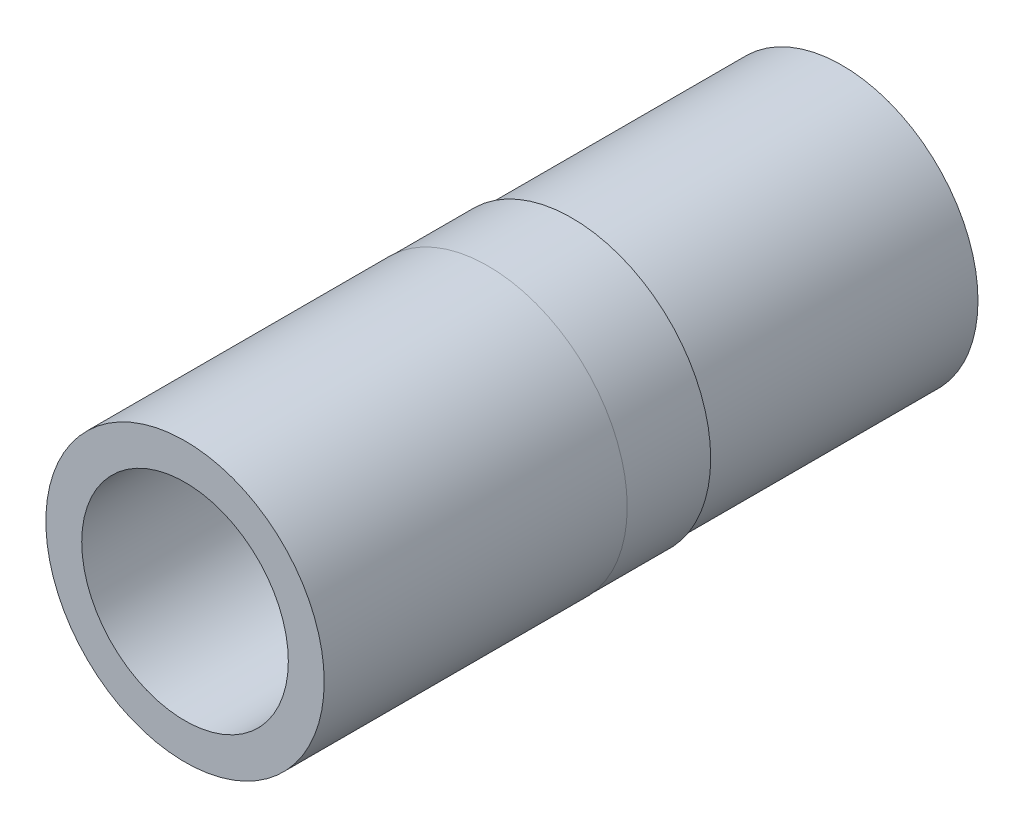
SolidWorks part; units mm, degrees
ref_plane "Front Plane" through (0, 0, 0) normal (0, 0, 1) x (1, 0, 0)
ref_plane "Top Plane" through (0, 0, 0) normal (0, 1, 0) x (1, 0, 0)
ref_plane "Right Plane" through (0, 0, 0) normal (1, 0, 0) x (0, 0, -1)
sketch "Sketch1" plane through (0, 0, 0) normal (0, 0, 1) x (1, 0, 0)
  circle A0 centre (0, 0) radius 25.795
  circle A1 centre (0, 0) radius 18.885
  dimension "D1" = 51.59
  dimension "D2" = 6.91
extrude "Boss-Extrude1" add sketch "Sketch1" along normal blind 67.2
sketch "Sketch2" plane through (0, 0, 0) normal (0, 0, -1) x (-1, 0, 0)
  circle A0 centre (0, 0) radius 21.795
  circle A1 centre (0, 0) radius 25.795 construction
  circle A2 centre (0, 0) radius 21.195
  dimension "D1" = 4
  dimension "D2" = 4.6
extrude "Cut-Extrude2" cut sketch "Sketch2" against normal blind 10.73
sketch "Sketch3" plane through (0, 0, 0) normal (0, 0, -1) x (-1, 0, 0)
  circle A0 centre (0, 0) radius 21.195
  circle A1 centre (0, 0) radius 18.885
extrude "Cut-Extrude3" cut sketch "Sketch3" against normal through all both and the other way through all
sketch "Sketch4" plane through (0, 0, 67.2) normal (0, 0, 1) x (1, 0, 0)
  circle A0 centre (0, 0) radius 26.36
  dimension "D1" = 52.72
extrude "Boss-Extrude2" add sketch "Sketch4" against normal blind 15.9
sketch "Sketch5" plane through (0, 0, 67.2) normal (0, 0, 1) x (1, 0, 0)
  circle A0 centre (0, 0) radius 26.415
  dimension "D1" = 52.83
extrude "Boss-Extrude3" add sketch "Sketch5" along normal blind 57.51
sketch "Sketch10" plane through (0, 0, 51.3) normal (0, 0, -1) x (-1, 0, 0)
  circle A0 centre (0, 0) radius 19.6077
extrude "Cut-Extrude6" cut sketch "Sketch10" against normal through all both and the other way through all
